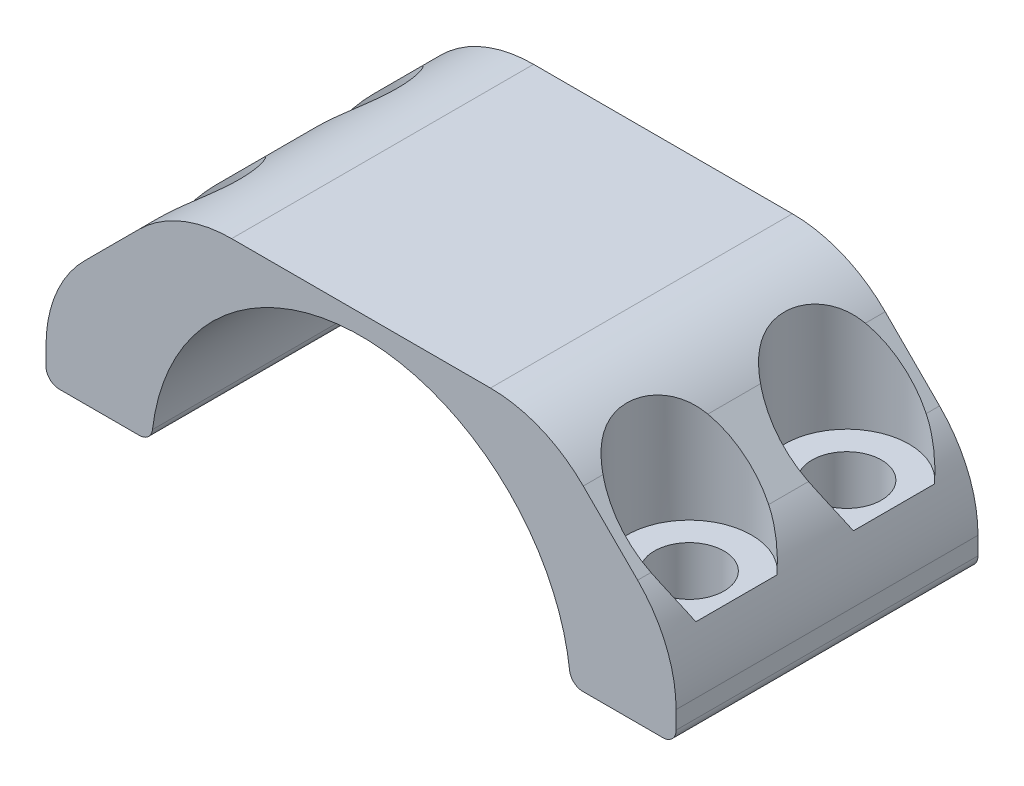
SolidWorks part; units mm, degrees
material "7075-T6 (SN)"
ref_plane "Front" through (0, 0, 0) normal (0, 0, 1) x (1, 0, 0)
ref_plane "Top" through (0, 0, 0) normal (0, 1, 0) x (1, 0, 0)
ref_plane "Right" through (0, 0, 0) normal (1, 0, 0) x (0, 0, -1)
sketch "Sketch1" plane through (0, 0, 0) normal (0, 0, 1) x (1, 0, 0)
  line L1 (-24, 17.5) -> (24, 17.5)
  line L2 (-24, 17.5) -> (-24, 0)
  line L3 (-24, 0) -> (24, 0)
  line L4 (24, 17.5) -> (24, 0)
  circle A0 centre (0, 0) radius 16
  point P7 (0, 0)
  dimension "D3" = 32
  dimension "D1" = 17.5
  dimension "D2" = 48
extrude "Boss-Extrude1" add sketch "Sketch1" along normal mid plane 23 contours A0 L3 L4 L1 L2
hole_wizard "CBORE for M5 SHCS1" positions "Sketch3" profile "Sketch2" counterbore size "M5" standard "ANSI Metric" end condition up to next
sketch "Sketch3" plane through (0, 17.5, 0) normal (0, 1, 0) x (1, 0, 0)
  line L0 (19.5, -6) -> (19.5, 6) construction
  line L3 (-19.5, -6) -> (-19.5, 6) construction
  line L6 (-19.5, 0) -> (19.5, 0) construction
  point P0 (-19.5, -6)
  point P2 (-19.5, 6)
  point P4 (19.5, -6)
  point P6 (19.5, 6)
  point P22 (0, 0)
  dimension "D1" = 39
  dimension "D2" = 12
sketch "Sketch2" plane through (-19.5, 17.5, 6) normal (1, 0, 0) x (0, 0, 1)
  line L0 (0, 0) -> (0, 17.5)
  line L1 (0, 17.5) -> (2.65, 17.5)
  line L3 (2.65, 17.5) -> (2.65, 10)
  line L4 (2.65, 10) -> (4.75, 10)
  line L5 (4.75, 10) -> (4.75, 0)
  line L7 (4.75, 0) -> (0, 0)
  line L11 (0, -6.35) -> (0, 107.95) construction
  dimension "Thru Hole Dia." = 5.3
  dimension "Thru Hole Depth" = 17.5
  dimension "C'Bore Dia." = 9.5
  dimension "C'Bore Depth" = 10
sketch "Sketch4" plane through (0, 0, 11.5) normal (0, 0, 1) x (1, 0, 0)
  line L0 (24, 17.5) -> (14, 17.5)
  line L1 (-24, 17.5) -> (24, 17.5) construction
  line L2 (14, 17.5) -> (24, 7.5)
  line L3 (24, 17.5) -> (24, 0) construction
  line L4 (24, 7.5) -> (24, 17.5)
  line L5 (-14, 17.5) -> (-24, 17.5)
  line L6 (-24, 17.5) -> (-24, 7.5)
  line L7 (-24, 17.5) -> (-24, 0) construction
  line L8 (-24, 7.5) -> (-14, 17.5)
  dimension "D1" = 10
extrude "Chamfer" cut sketch "Sketch4" against normal up to next
sketch "Sketch5" plane through (0, 0, 0) normal (0, -1, 0) x (-1, 0, 0)
  line L1 (24, -11.5) -> (-24, -11.5)
  line L2 (24, -11.5) -> (24, 11.5)
  line L3 (24, 11.5) -> (-24, 11.5)
  line L4 (-24, -11.5) -> (-24, 11.5)
extrude "Cut-Extrude2" cut sketch "Sketch5" against normal blind 1
sketch "Sketch6" plane through (0, 0, 11.5) normal (0, 0, 1) x (1, 0, 0)
  line L0 (-24, 3.3579) -> (-24, 7.5)
  line L1 (-24, 7.5) -> (-21.0711, 10.4289)
  line L2 (-16.9289, 14.5711) -> (-14, 17.5)
  line L3 (-14, 17.5) -> (-9.8579, 17.5)
  line L4 (9.8579, 17.5) -> (14, 17.5)
  line L5 (14, 17.5) -> (16.9289, 14.5711)
  line L6 (21.0711, 10.4289) -> (24, 7.5)
  line L7 (-24, 7.5) -> (-24, 1)
  line L8 (-24, 1) -> (-15.9687, 1)
  line L9 (15.9687, 1) -> (24, 1)
  line L10 (24, 1) -> (24, 7.5)
  line L11 (24, 7.5) -> (14, 17.5)
  line L12 (14, 17.5) -> (-14, 17.5)
  line L13 (-14, 17.5) -> (-24, 7.5)
  line L14 (-24, 3.3579) -> (-24, 1) construction
  line L15 (-24, 1) -> (-15.9687, 1) construction
  line L16 (15.9687, 1) -> (24, 1) construction
  line L17 (24, 1) -> (24, 3.3579) construction
  line L18 (21.0711, 10.4289) -> (16.9289, 14.5711) construction
  line L19 (9.8579, 17.5) -> (-9.8579, 17.5) construction
  line L20 (-16.9289, 14.5711) -> (-21.0711, 10.4289) construction
  line L21 (14, 17.5) -> (24, 7.5) construction
  line L22 (24, 7.5) -> (24, 3.3579)
  arc A0 (-24, 3.3579) -> (-21.0711, 10.4289) centre (-14, 3.3579) cw
  arc A1 (15.9687, 1) -> (-15.9687, 1) centre (0, 0) ccw
  arc A2 (15.9687, 1) -> (-15.9687, 1) centre (0, 0) ccw construction
  arc A3 (24, 3.3579) -> (21.0711, 10.4289) centre (14, 3.3579) ccw
  arc A4 (16.9289, 14.5711) -> (9.8579, 17.5) centre (9.8579, 7.5) ccw
  arc A5 (-9.8579, 17.5) -> (-16.9289, 14.5711) centre (-9.8579, 7.5) ccw
  dimension "D2" = 10
  dimension "D1" = 0
extrude "Cut-Extrude3" cut sketch "Sketch6" against normal through all both and the other way through all
fillet "Fillet1" radius 1 4 edges at (-24, 1, 0) (24, 1, 0) (-15.9687, 1, 0) (15.9687, 1, 0)
